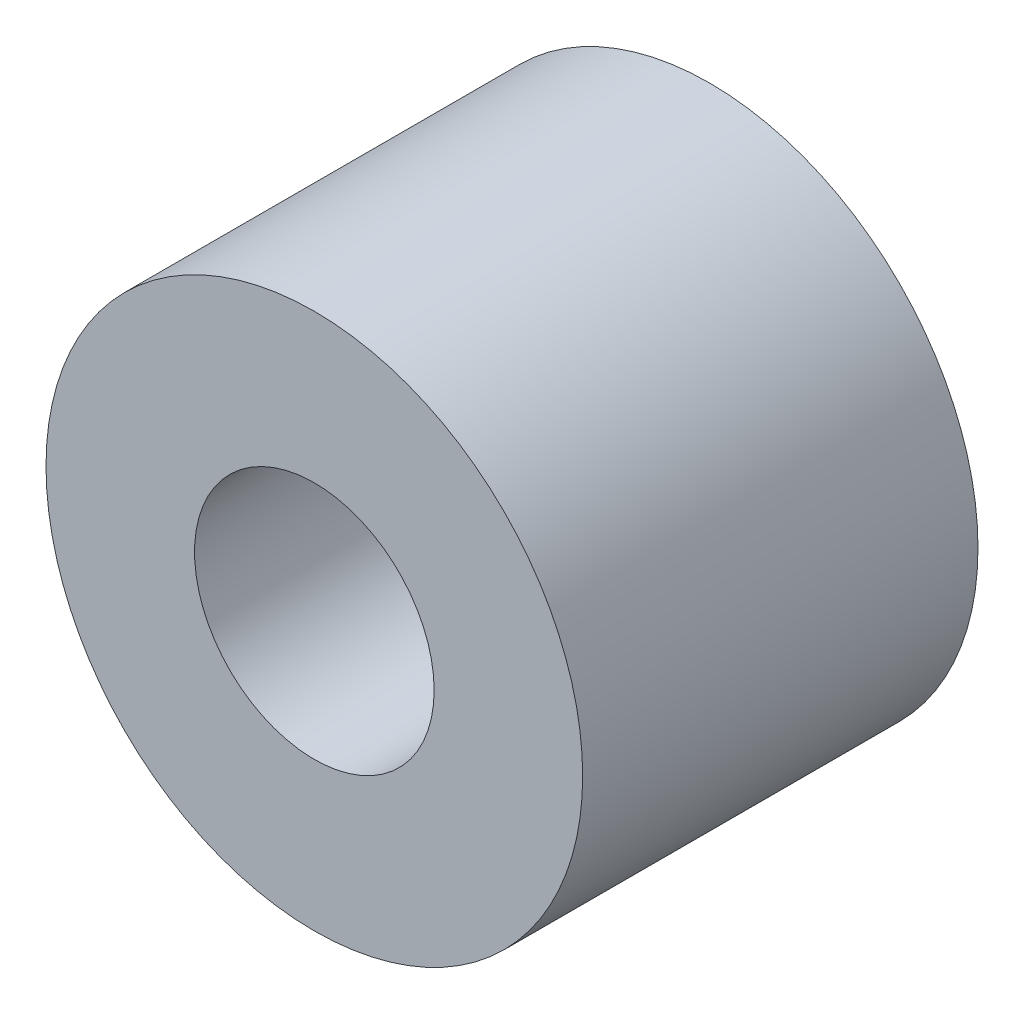
SolidWorks part; units mm, degrees
ref_plane "Front Plane" through (0, 0, 0) normal (0, 0, 1) x (1, 0, 0)
ref_plane "Top Plane" through (0, 0, 0) normal (0, 1, 0) x (1, 0, 0)
ref_plane "Right Plane" through (0, 0, 0) normal (1, 0, 0) x (0, 0, -1)
sketch "Sketch1" plane through (0, 0, 0) normal (0, 0, 1) x (1, 0, 0)
  circle A0 centre (0, 0) radius 14.224
  circle A1 centre (0, 0) radius 6.35
  dimension "D1" = 12.7
  dimension "D2" = 28.448
extrude "Boss-Extrude1" add sketch "Sketch1" along normal blind 20.955
